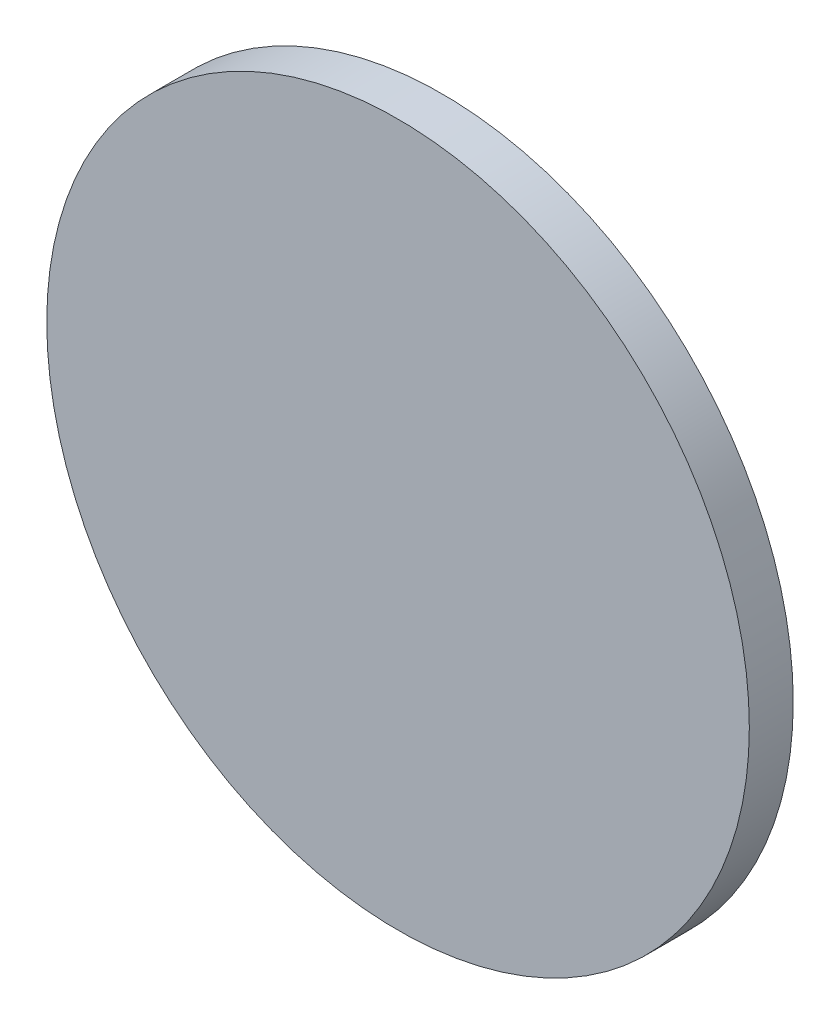
SolidWorks part; units mm, degrees
ref_plane "Plan de face" through (0, 0, 0) normal (0, 0, 1) x (1, 0, 0)
ref_plane "Plan de dessus" through (0, 0, 0) normal (0, 1, 0) x (1, 0, 0)
ref_plane "Plan de droite" through (0, 0, 0) normal (1, 0, 0) x (0, 0, -1)
sketch "Esquisse1" plane through (0, 0, 0) normal (0, 0, 1) x (1, 0, 0)
  circle A0 centre (0, 0) radius 12
  dimension "D1" = 24
extrude "Boss.-Extru.1" add sketch "Esquisse1" along normal blind 1.5
